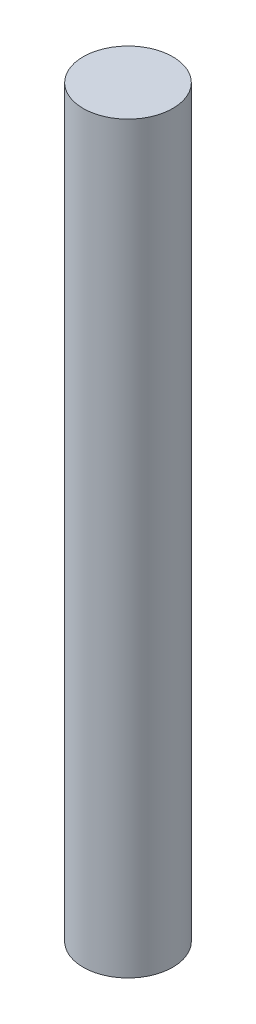
SolidWorks part; units mm, degrees
ref_plane "Front Plane" through (0, 0, 0) normal (0, 0, 1) x (1, 0, 0)
ref_plane "Top Plane" through (0, 0, 0) normal (0, 1, 0) x (1, 0, 0)
ref_plane "Right Plane" through (0, 0, 0) normal (1, 0, 0) x (0, 0, -1)
sketch "Sketch1" plane through (0, 0, 0) normal (0, 1, 0) x (1, 0, 0)
  circle A0 centre (0, 0) radius 15
  dimension "D1" = 30
extrude "Boss-Extrude1" add sketch "Sketch1" along normal blind 249
